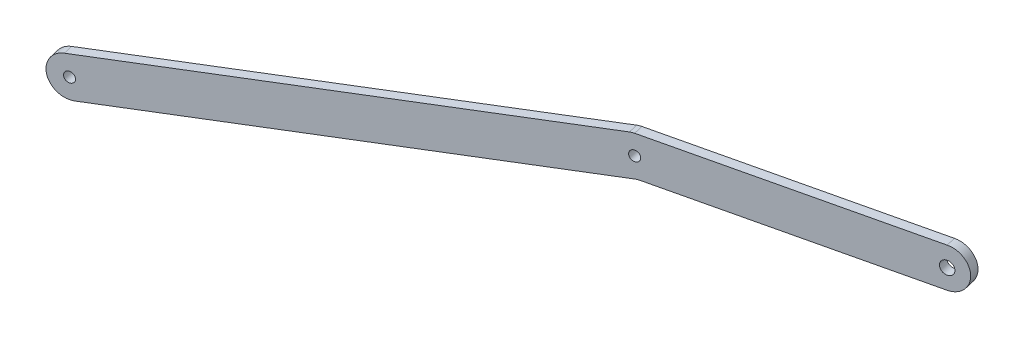
SolidWorks part; units mm, degrees
ref_plane "Front Plane" through (0, 0, 0) normal (0, 0, 1) x (1, 0, 0)
ref_plane "Top Plane" through (0, 0, 0) normal (0, 1, 0) x (1, 0, 0)
ref_plane "Right Plane" through (0, 0, 0) normal (1, 0, 0) x (0, 0, -1)
sketch3d "3DSketch1"
  line L0 (0, 0, 0) -> (296.9627, 69.39, -69.6739)
  line L1 (296.9627, 69.39, -69.6739) -> (461.1947, 69.39, -108.2063)
ref_plane "Plane1" through (0, 0, 0) normal (-0.2284, 0, -0.9736) x (-0.9736, 0, 0.2284)
sketch "Sketch1" plane through (0, 0, 0) normal (-0.2284, 0, -0.9736) x (-0.9736, 0, 0.2284)
  line L0 (2.8171, 12.3836) -> (-302.2095, 81.7736)
  line L1 (-305.0267, 82.09) -> (-473.7184, 82.09)
  line L2 (-473.7184, 56.69) -> (-307.8793, 56.69)
  line L4 (-305.0622, 56.3736) -> (-2.8171, -12.3836)
  circle A0 centre (0, 0) radius 3.2639
  circle A1 centre (-305.0267, 69.39) radius 3.2639
  circle A2 centre (-473.7184, 69.39) radius 4.1999
  circle A3 centre (0, 0) radius 12.7
  circle A4 centre (-305.0267, 69.39) radius 12.7
  circle A5 centre (-473.7184, 69.39) radius 12.7
  arc A6 (-305.0622, 56.3736) -> (-307.8793, 56.69) centre (-307.8793, 43.99) ccw
  dimension "D1" = 6.5278
  dimension "D2" = 8.3998
  dimension "D3" = 25.4
extrude "Boss-Extrude1" add sketch "Sketch1" along normal mid plane 6.35 contours A3 A0 | A6 L4 A3 L0 A4 L1 A5 L2 | A5 A2 | A4 A1
